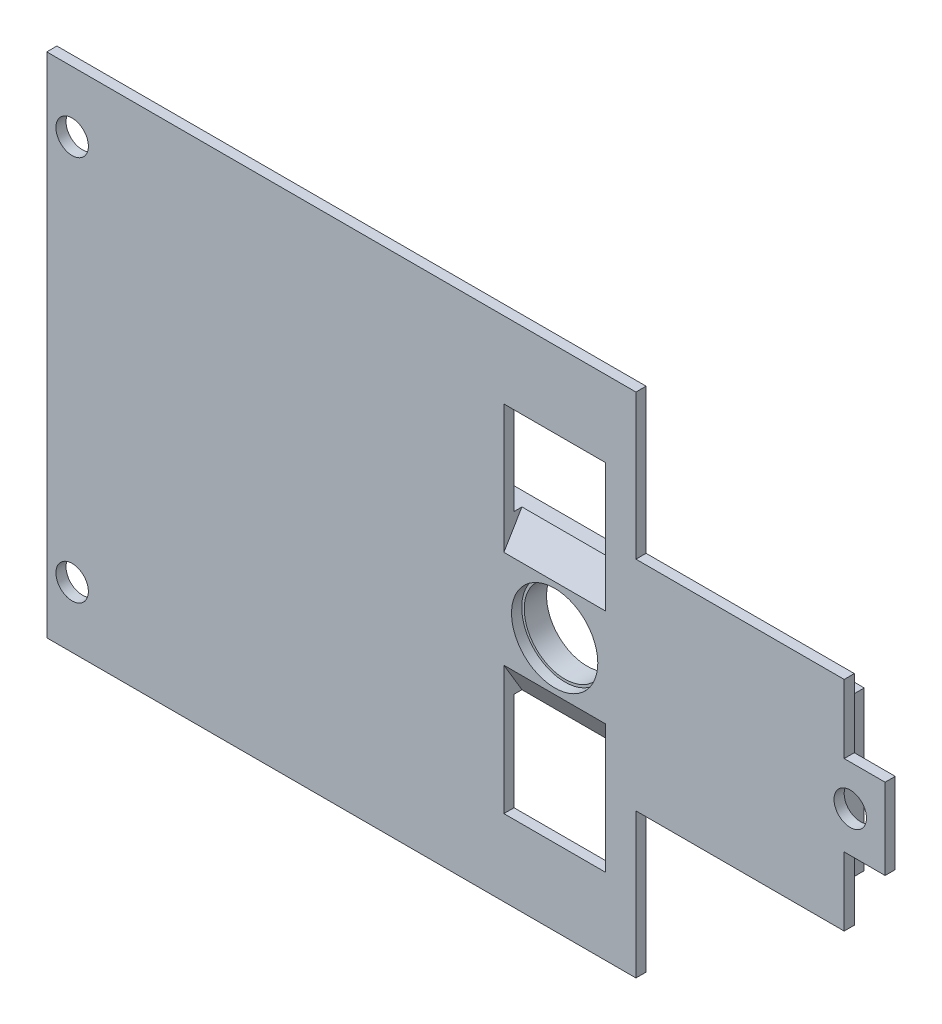
SolidWorks part; units mm, degrees
ref_plane "Front Plane" through (0, 0, 0) normal (0, 0, 1) x (1, 0, 0)
ref_plane "Top Plane" through (0, 0, 0) normal (0, 1, 0) x (1, 0, 0)
ref_plane "Right Plane" through (0, 0, 0) normal (1, 0, 0) x (0, 0, -1)
sketch "Sketch4" plane through (0, 0, 0) normal (0, 0, 1) x (1, 0, 0)
  line L0 (-50.0428, 25) -> (8.0068, 25)
  line L1 (8.0068, 25) -> (8.0068, 10.7378)
  line L2 (8.0068, 10.7378) -> (28.5244, 10.7378)
  line L3 (28.5244, 10.7378) -> (28.5244, 3.982)
  line L4 (0, 0) -> (-58.4806, 0) construction
  line L5 (28.5244, 3.982) -> (32.5554, 3.982)
  line L7 (32.5554, 3.982) -> (32.5554, -3.982)
  line L9 (32.5554, -3.982) -> (28.5244, -3.982)
  line L10 (28.5244, -3.982) -> (28.5244, -10.7378)
  line L11 (28.5244, -10.7378) -> (8.0068, -10.7378)
  line L12 (8.0068, -10.7378) -> (8.0068, -25)
  line L13 (8.0068, -25) -> (-50.0428, -25)
  line L14 (-50.0428, -25) -> (-50.0428, 25)
  line L15 (-5.0043, 17.4777) -> (-5.0043, -17.4777) construction
  line L16 (-5.0043, -17.4777) -> (5.0043, -17.4777) construction
  line L17 (5.0043, -17.4777) -> (5.0043, 17.4777) construction
  line L18 (5.0043, 17.4777) -> (-5.0043, 17.4777) construction
  line L19 (-5.0043, 6.0051) -> (5.0043, 6.0051) construction
  line L21 (-5.0043, -6.0051) -> (5.0043, -6.0051) construction
  line L23 (-10.1394, 8.0068) -> (27.5235, 8.0068) construction
  line L24 (27.5235, 8.0068) -> (27.5235, -8.0068) construction
  line L25 (27.5235, -8.0068) -> (-10.1394, -8.0068) construction
  line L28 (-42.7789, -23.0197) -> (-8.0068, -23.0197) construction
  circle A0 centre (-47.5428, 19) radius 1.6
  circle A1 centre (-47.5428, -19) radius 1.6
  circle A2 centre (29.1235, 0) radius 1.6
  dimension "D1" = 38
  dimension "D3" = 3.2
  dimension "D5" = 3.2
  dimension "D2" = 2.5
  dimension "D4" = 50
extrude "Boss-Extrude2" add sketch "Sketch4" along normal blind 1
sketch "Sketch5" plane through (0, 0, 0) normal (0, 0, -1) x (-1, 0, 0)
  line L5 (10.1307, 7.8) -> (-27.3, 7.8)
  line L7 (-37.7756, 0) -> (61.1931, 0) construction
  line L8 (10.4164, 22.8) -> (42.5753, 22.8)
  line L10 (42.5753, 22.8) -> (42.5753, 12.3)
  line L11 (50.0428, -25) -> (-8.0068, -25) construction
  line L12 (10.4164, -25) -> (42.5753, -25)
  line L13 (-8.0068, 25) -> (50.0428, 25) construction
  line L14 (10.4164, 22.8) -> (10.4164, 8)
  line L17 (10.4164, -8) -> (10.4164, -25)
  line L18 (-27.3, 7.8) -> (-27.3, -7.8)
  line L19 (-27.3, -7.8) -> (10.1307, -7.8)
  line L27 (10.1307, 7.8) -> (10.6164, 7.8) construction
  line L28 (10.6164, 22.6) -> (10.6164, 7.8) construction
  line L29 (10.1307, -7.8) -> (10.6164, -7.8) construction
  line L30 (10.6164, -7.8) -> (10.6164, -24.8) construction
  line L31 (10.6164, -24.8) -> (42.3753, -24.8) construction
  line L32 (42.3753, 22.6) -> (42.3753, -24.8) construction
  line L33 (10.6164, 22.6) -> (42.3753, 22.6) construction
  line L34 (10.1307, 7.8) -> (10.4164, 7.8)
  line L35 (10.4164, 7.8) -> (10.4164, 8)
  line L36 (-27.5, 8) -> (-27.5, -8) construction
  line L37 (10.1307, 8) -> (10.4164, 8) construction
  line L38 (10.1307, 8) -> (-27.5, 8) construction
  line L39 (-27.5, -8) -> (10.1307, -8) construction
  line L40 (10.1307, -8) -> (10.4164, -8) construction
  line L41 (10.1307, -7.8) -> (10.4164, -7.8)
  line L42 (10.4164, -7.8) -> (10.4164, -8)
  line L43 (42.5753, 12.3) -> (50.0428, 12.3)
  line L44 (50.0428, -25) -> (50.0428, 25) construction
  line L45 (50.0428, 12.3) -> (50.0428, -12.3)
  line L46 (42.5753, -12.3) -> (42.5753, -25)
  line L47 (42.5753, 22.8) -> (42.5753, -25) construction
  line L48 (42.5753, -12.3) -> (50.0428, -12.3)
  point P38 (50.0428, 0)
  dimension "D1" = 2.2
  dimension "D2" = 0.2
  dimension "D3" = 24.6
extrude "Boss-Extrude3" add sketch "Sketch5" along normal blind 2.2
sketch "Sketch6" plane through (0, 0, 1) normal (0, 0, 1) x (1, 0, 0)
  line L0 (-5.0043, 17.4777) -> (-5.0043, -17.4777) construction
  line L5 (-5.0043, -8.0068) -> (5.0043, -8.0068)
  line L6 (-5.0043, -8.0068) -> (-5.0043, -17.4777)
  line L7 (-5.0043, -17.4777) -> (5.0043, -17.4777)
  line L8 (5.0043, -8.0068) -> (5.0043, -17.4777)
  line L9 (27.5235, -8.0068) -> (-10.1394, -8.0068) construction
  line L10 (5.0043, -17.4777) -> (5.0043, 17.4777) construction
  line L11 (-5.0043, 17.4777) -> (5.0043, 17.4777)
  line L12 (-5.0043, 17.4777) -> (-5.0043, 8.0068)
  line L13 (-5.0043, 8.0068) -> (5.0043, 8.0068)
  line L14 (5.0043, 17.4777) -> (5.0043, 8.0068)
  line L15 (-10.1394, 8.0068) -> (27.5235, 8.0068) construction
  circle A0 centre (0, 0) radius 4
  dimension "D1" = 8
extrude "Cut-Extrude1" cut sketch "Sketch6" against normal through all
sketch "Sketch7" plane through (-5.0043, 0, 0) normal (1, 0, 0) x (0, 0, -1)
  line L0 (0.9044, -8.0068) -> (-1, -4.8142)
  line L1 (0, -8.0068) -> (-1, -8.0068) construction
  line L2 (-1, -10.7378) -> (-1, -3.982) construction
  line L3 (-1, -4.8142) -> (-1, -8.0068)
  line L5 (-1, -8.0068) -> (0, -8.0068)
  line L8 (0, -8.0068) -> (0.9044, -8.0068)
  dimension "D2" = 30.816
extrude "Cut-Extrude2" cut sketch "Sketch7" along normal up to surface (10.0086 mm away) up to face at (5.0043, -12.7423, 0.5)
mirror "Mirror1" about plane through (0, 0, 0) normal (0, 1, 0) of "Cut-Extrude2"
sketch "Sketch8" plane through (0, 0, -2.2) normal (0, 0, -1) x (-1, 0, 0)
  line L0 (42.5753, -12.3) -> (50.0428, -12.3) construction
  line L1 (50.0428, 12.3) -> (47.5428, 12.3)
  line L2 (50.0428, 12.3) -> (50.0428, -12.3)
  line L3 (50.0428, -12.3) -> (47.5428, -12.3)
  line L4 (47.5428, 12.3) -> (47.5428, -12.3)
  line L5 (50.0428, -25) -> (50.0428, 25) construction
  dimension "D1" = 2.5
extrude "Boss-Extrude4" add sketch "Sketch8" along normal blind 10
sketch "Sketch9" plane through (-50.0428, 0, 0) normal (-1, 0, 0) x (0, 0, 1)
  line L0 (-9.2, 9.0613) -> (-12.2, 9.0613)
  line L1 (-12.2, -12.3) -> (-12.2, 12.3) construction
  line L2 (-12.2, 9.0613) -> (-12.2, 5.0871)
  line L3 (-12.2, 5.0871) -> (-9.2, 5.0871)
  arc A0 (-9.2, 5.0871) -> (-9.2, 9.0613) centre (-9.2, 7.0742) ccw
  dimension "D1" = 3
extrude "Cut-Extrude3" cut sketch "Sketch9" against normal up to next
sketch "Sketch10" plane through (0, 0, 1) normal (0, 0, 1) x (1, 0, 0)
  circle A0 centre (0, 0) radius 4.25
  dimension "D1" = 8.5
extrude "Cut-Extrude4" cut sketch "Sketch10" against normal blind 1
